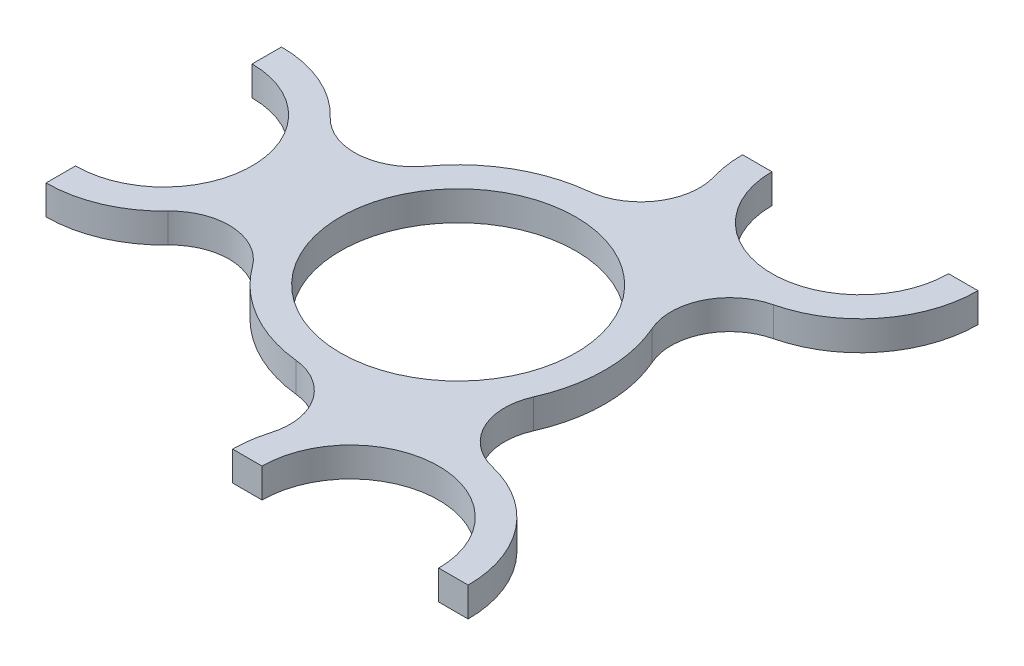
SolidWorks part; units mm, degrees
ref_plane "Front Plane" through (0, 0, 0) normal (0, 0, 1) x (1, 0, 0)
ref_plane "Top Plane" through (0, 0, 0) normal (0, 1, 0) x (1, 0, 0)
ref_plane "Right Plane" through (0, 0, 0) normal (1, 0, 0) x (0, 0, -1)
sketch "Sketch1" plane through (0, 0, 0) normal (0, 1, 0) x (1, 0, 0)
  line L0 (0, 0) -> (-100, 0) construction
  line L1 (-100, 40) -> (-100, 30)
  line L4 (-100, -30) -> (-100, -40)
  line L5 (0, 74.4028) -> (0, -84.2666) construction
  line L6 (10, 86.6) -> (20, 86.6)
  line L7 (80, 86.6) -> (90, 86.6)
  line L8 (80, -86.6) -> (90, -86.6)
  line L9 (10, -86.6) -> (20, -86.6)
  circle A6 centre (0, 0) radius 40
  arc A7 (-40.3571, -29.5178) -> (-5.3851, -49.7092) centre (0, 0) ccw
  arc A8 (-100, -30) -> (-100, 30) centre (-100, 0) ccw
  arc A9 (-100, -40) -> (-71, -27.55) centre (-100, 0) ccw
  arc A10 (-71, 27.55) -> (-40.3571, 29.5178) centre (-56.5, 41.3249) ccw
  arc A11 (-71, -27.55) -> (-40.3571, -29.5178) centre (-56.5, -41.3249) cw
  arc A12 (-71, 27.55) -> (-100, 40) centre (-100, 0) ccw
  arc A13 (20, 86.6) -> (80, 86.6) centre (50, 86.6) ccw
  arc A14 (10, 86.6) -> (11.6406, 75.2619) centre (50, 86.6) ccw
  arc A15 (-5.3851, 49.7092) -> (11.6406, 75.2619) centre (-7.5392, 69.5928) ccw
  arc A16 (59.3596, 47.7104) -> (45.7425, 20.1898) centre (64.0395, 28.2657) ccw
  arc A17 (-5.3851, 49.7092) -> (-40.3571, 29.5178) centre (0, 0) ccw
  arc A18 (59.3596, 47.7104) -> (90, 86.6) centre (50, 86.6) ccw
  arc A19 (59.3596, -47.7104) -> (45.7425, -20.1898) centre (64.0395, -28.2657) cw
  arc A20 (59.3596, -47.7104) -> (90, -86.6) centre (50, -86.6) cw
  arc A21 (20, -86.6) -> (80, -86.6) centre (50, -86.6) cw
  arc A22 (10, -86.6) -> (11.6406, -75.2619) centre (50, -86.6) cw
  arc A23 (-5.3851, -49.7092) -> (11.6406, -75.2619) centre (-7.5392, -69.5928) cw
  arc A24 (45.7425, -20.1898) -> (45.7425, 20.1898) centre (0, 0) ccw
  dimension "D1" = 80
  dimension "D2" = 100
  dimension "D3" = 100
  dimension "D4" = 80
  dimension "D5" = 60
  dimension "D6" = 40
  dimension "D7" = 86.6
  dimension "D9" = 40
  dimension "D10" = 40
  dimension "D11" = 80
  dimension "D12" = 60
  dimension "D8" = 50
extrude "Boss-Extrude1" add sketch "Sketch1" along normal blind 10
